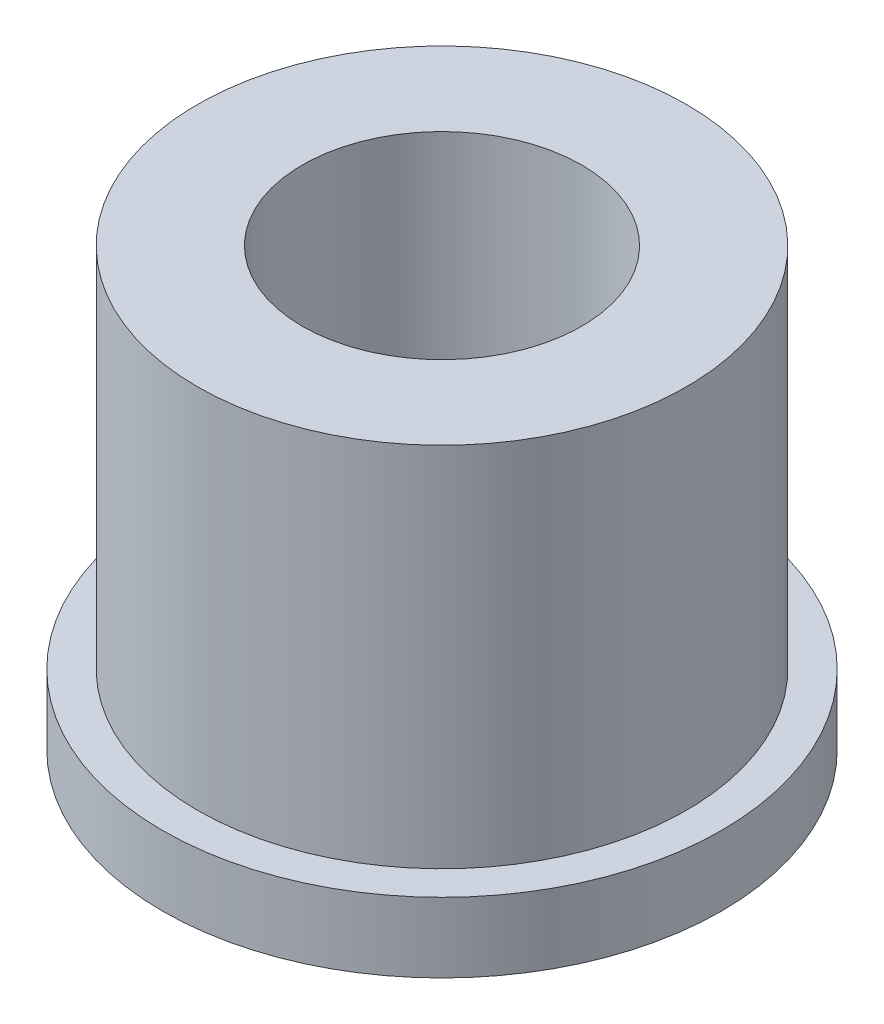
SolidWorks part; units mm, degrees
material "Phosphor bronze 10% D, UNS C52400"
ref_plane "Front Plane" through (0, 0, 0) normal (0, 0, 1) x (1, 0, 0)
ref_plane "Top Plane" through (0, 0, 0) normal (0, 1, 0) x (1, 0, 0)
ref_plane "Right Plane" through (0, 0, 0) normal (1, 0, 0) x (0, 0, -1)
sketch "Sketch1" plane through (0, 0, 0) normal (0, 1, 0) x (1, 0, 0)
  circle A0 centre (0, 0) radius 2
  circle A1 centre (0, 0) radius 3.5
  dimension "D1" = 4
  dimension "D2" = 7
extrude "Boss-Extrude1" add sketch "Sketch1" along normal blind 6.25
sketch "Sketch2" plane through (0, 0, 0) normal (0, -1, 0) x (1, 0, 0)
  circle A0 centre (0, 0) radius 2 construction
  circle A1 centre (0, 0) radius 2
  circle A2 centre (0, 0) radius 4
  dimension "D1" = 2
extrude "Boss-Extrude2" add sketch "Sketch2" against normal blind 1
